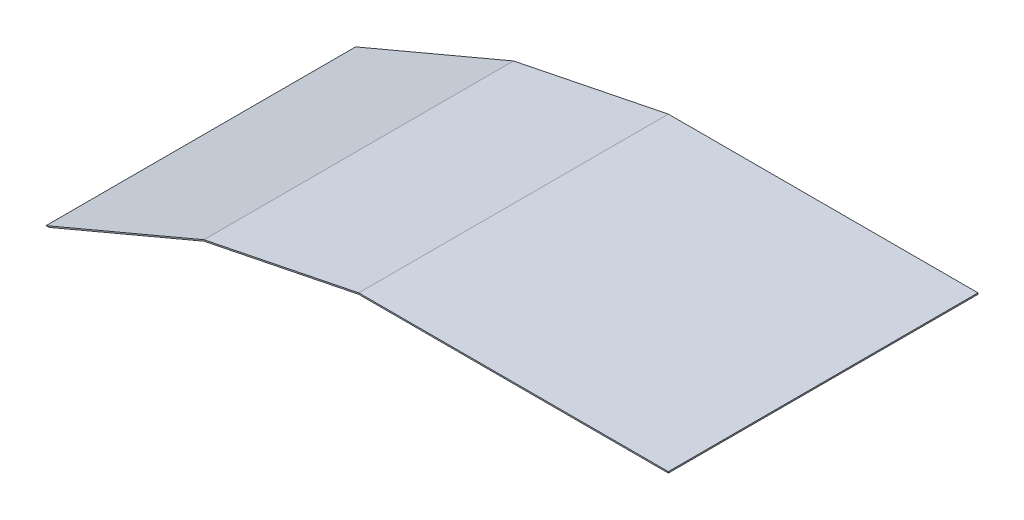
SolidWorks part; units mm, degrees
ref_plane "前视基准面" through (0, 0, 0) normal (0, 0, 1) x (1, 0, 0)
ref_plane "上视基准面" through (0, 0, 0) normal (0, 1, 0) x (1, 0, 0)
ref_plane "右视基准面" through (0, 0, 0) normal (1, 0, 0) x (0, 0, -1)
other "Configuration Table"
sketch "草图1" plane through (0, 0, 0) normal (0, 0, 1) x (1, 0, 0)
  line L0 (0, 0) -> (0, 77.2574) construction
  line L1 (0, 0) -> (-200, 0) construction
  line L2 (-200, 0) -> (-150, 21.1397)
  line L6 (-200, 0) -> (-201, 0)
  line L7 (-201, 0) -> (-150, 21.5625)
  line L8 (-150, 21.5625) -> (-100, 31.698)
  line L10 (-150, 21.1397) -> (-100, 31.2752)
  line L11 (-100, 31.2752) -> (0, 31.2752)
  line L12 (-100, 31.698) -> (0, 31.698)
  line L13 (0, 31.698) -> (0, 31.2752)
  dimension "D1" = 22.918
  dimension "D2" = 50
  dimension "D3" = 11.459
  dimension "D4" = 1
  dimension "D5" = 50
  dimension "D6" = 100
extrude "凸台-拉伸1" add sketch "草图1" along normal blind 100
